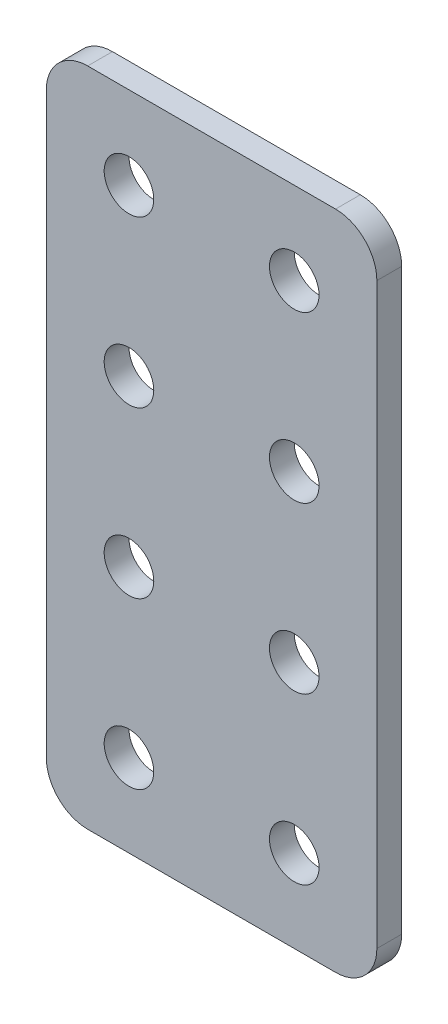
SolidWorks part; units mm, degrees
ref_plane "Płaszczyzna przednia" through (0, 0, 0) normal (0, 0, 1) x (1, 0, 0)
ref_plane "Płaszczyzna górna" through (0, 0, 0) normal (0, 1, 0) x (1, 0, 0)
ref_plane "Płaszczyzna prawa" through (0, 0, 0) normal (1, 0, 0) x (0, 0, -1)
sketch "Szkic1" plane through (0, 0, 0) normal (0, 0, 1) x (1, 0, 0)
  line L1 (-26.4908, 37.4118) -> (13.5092, 37.4118)
  line L2 (-26.4908, 37.4118) -> (-26.4908, -2.5882)
  line L3 (-26.4908, -2.5882) -> (13.5092, -2.5882)
  line L4 (13.5092, 37.4118) -> (13.5092, -2.5882)
  circle A0 centre (-16.4908, 27.4118) radius 3
  circle A1 centre (3.5092, 27.4118) radius 3
  circle A2 centre (-16.4908, 7.4118) radius 3
  circle A3 centre (3.5092, 7.4118) radius 3
  dimension "D11" = 6
  dimension "D12" = 6
  dimension "D13" = 6
  dimension "D14" = 6
  dimension "D1" = 40
  dimension "D2" = 40
  dimension "D3" = 10
  dimension "D4" = 10
  dimension "D5" = 10
  dimension "D6" = 10
  dimension "D7" = 10
  dimension "D8" = 10
  dimension "D9" = 10
  dimension "D10" = 10
extrude "Dodanie-wyciągnięcie1" add sketch "Szkic1" along normal blind 3
mirror "Lustro2" about plane through (-26.4908, -2.5882, 3) normal (0, 1, 0) of "Dodanie-wyciągnięcie1"
fillet "Zaokrąglenie1" radius 5 4 edges at (13.5092, 37.4118, 1.5) (-26.4908, 37.4118, 1.5) (13.5092, -42.5882, 1.5) (-26.4908, -42.5882, 1.5)
